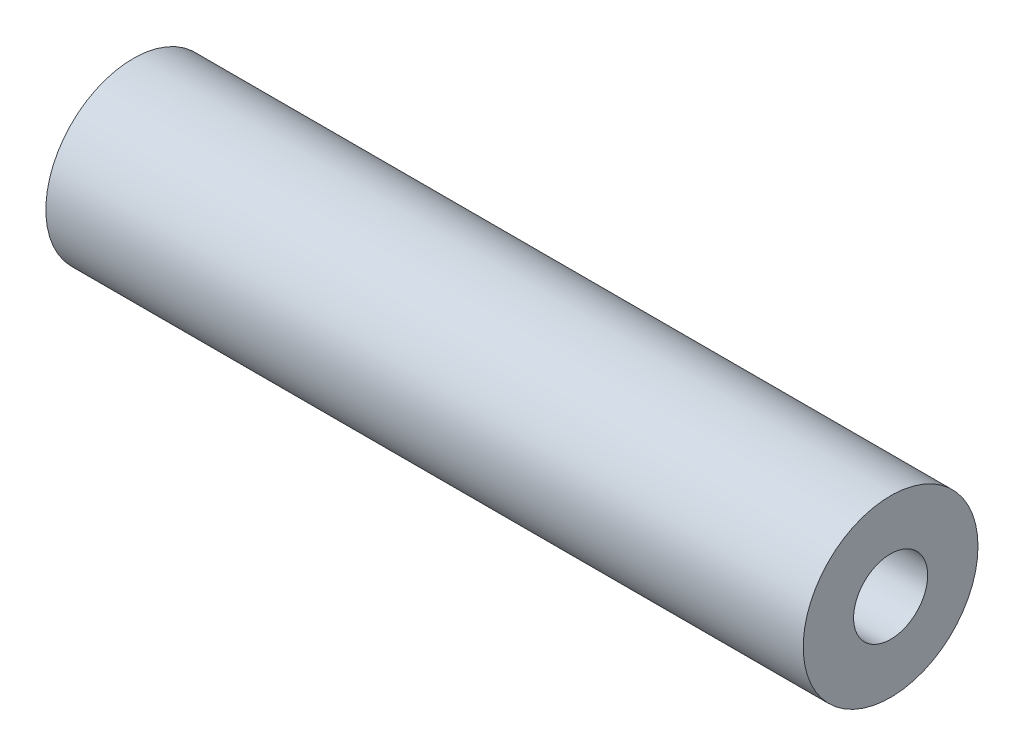
SolidWorks part; units mm, degrees
material "6061-T6 (SS)"
ref_plane "Front Plane" through (0, 0, 0) normal (0, 0, 1) x (1, 0, 0)
ref_plane "Top Plane" through (0, 0, 0) normal (0, 1, 0) x (1, 0, 0)
ref_plane "Right Plane" through (0, 0, 0) normal (1, 0, 0) x (0, 0, -1)
sketch "Sketch1" plane through (0, 0, 0) normal (1, 0, 0) x (0, 0, -1)
  circle A0 centre (0, 0) radius 4.7625
  dimension "D1" = 9.525
extrude "Boss-Extrude1" add sketch "Sketch1" along normal mid plane 41.275
hole_wizard "#10-32 Tapped Hole1" positions "3DSketch1" profile "Sketch2" tap size "#10-32" standard "ANSI Inch"
sketch3d "3DSketch1"
  line L0 (20.6375, 0, 0) -> (-20.6375, 0, 0) construction
  point P0 (20.6375, 0, 0)
  point P4 (-20.6375, 0, 0)
sketch "Sketch2" plane through (20.6375, 0, 0) normal (0, 1, 0) x (0, 0, -1)
  line L0 (0, 0) -> (0, 17.4693)
  line L1 (0, 17.4693) -> (2.0193, 16.256)
  line L2 (2.0193, 16.256) -> (2.0193, 0)
  line L5 (2.0193, 0) -> (0, 0)
  line L10 (0, 17.4693) -> (-2.0193, 16.256) construction
  line L11 (0, -6.35) -> (0, 107.95) construction
  dimension "Tap Drill Dia." = 4.0386
  dimension "Tap Drill Depth" = 16.256
  dimension "Drill Angle" = 118
cosmetic thread "Hole Thread1"
cosmetic thread "Hole Thread2"
